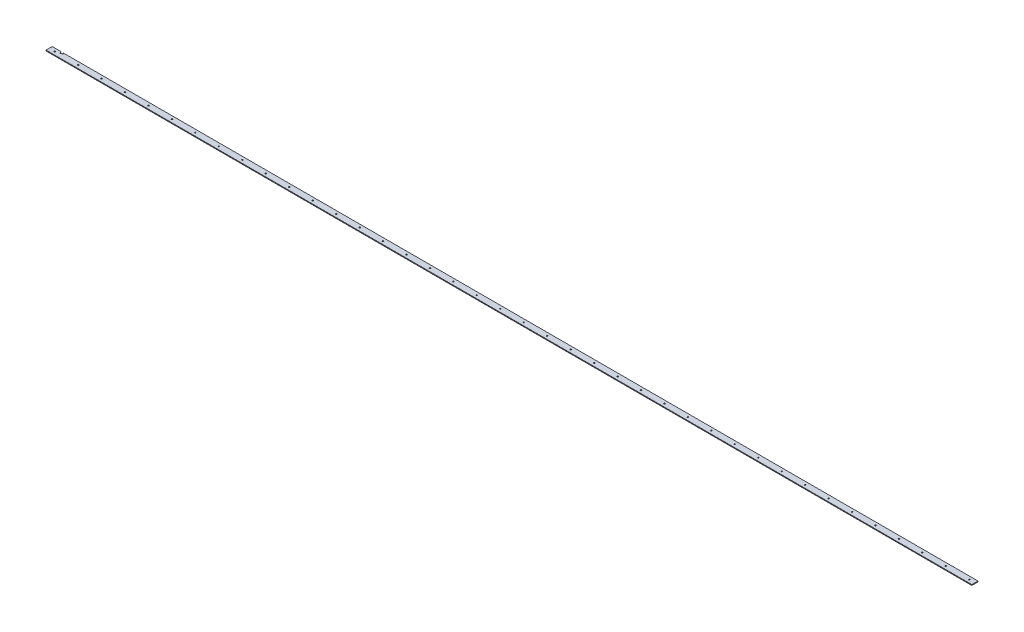
SolidWorks part; units mm, degrees
ref_plane "Ön Düzlem" through (0, 0, 0) normal (0, 0, 1) x (1, 0, 0)
ref_plane "Üst Düzlem" through (0, 0, 0) normal (0, 1, 0) x (1, 0, 0)
ref_plane "Sağ Düzlem" through (0, 0, 0) normal (1, 0, 0) x (0, 0, -1)
sketch "Çizim1" plane through (0, 0, 0) normal (0, 1, 0) x (1, 0, 0)
  line L1 (-3000, -20) -> (3000, -20)
  line L2 (-3000, -20) -> (-3000, 20)
  line L3 (-3000, 20) -> (3000, 20)
  line L4 (3000, -20) -> (3000, 20)
  line L5 (-3000, -20) -> (3000, 20) construction
  line L6 (-3000, 20) -> (3000, -20) construction
  point P0 (0, 0)
  dimension "D1" = 6000
  dimension "D2" = 40
extrude "Yükseklik-Ekstrüzyon1" add sketch "Çizim1" along normal blind 5
sketch "Çizim2" plane through (0, 5, 0) normal (0, 1, 0) x (1, 0, 0)
  line L0 (-3000, 20) -> (-3000, -20) construction
  line L1 (3000, 20) -> (-3000, 20) construction
  circle A0 centre (-2964, 0) radius 4
  dimension "D1" = 36
  dimension "D2" = 20
extrude "Kes-Ekstrüzyon1" cut sketch "Çizim2" against normal blind 5
pattern_linear "LÇoğaltma1" count 40 spacing 152 along (1, 0, 0) of "Kes-Ekstrüzyon1"
sketch "Çizim3" plane through (0, 5, 0) normal (0, 1, 0) x (1, 0, 0)
  line L0 (-2943.5701, 20) -> (-2936.1118, 6.4013)
  line L1 (3000, 20) -> (-3000, 20) construction
  line L2 (-2936.1118, 6.4013) -> (-2919.0839, 15.7404)
  line L3 (-2919.0839, 15.7404) -> (-2929.5858, 20)
  line L4 (-2929.5858, 20) -> (-2943.5701, 20)
extrude "Kes-Ekstrüzyon2" cut sketch "Çizim3" against normal blind 5
